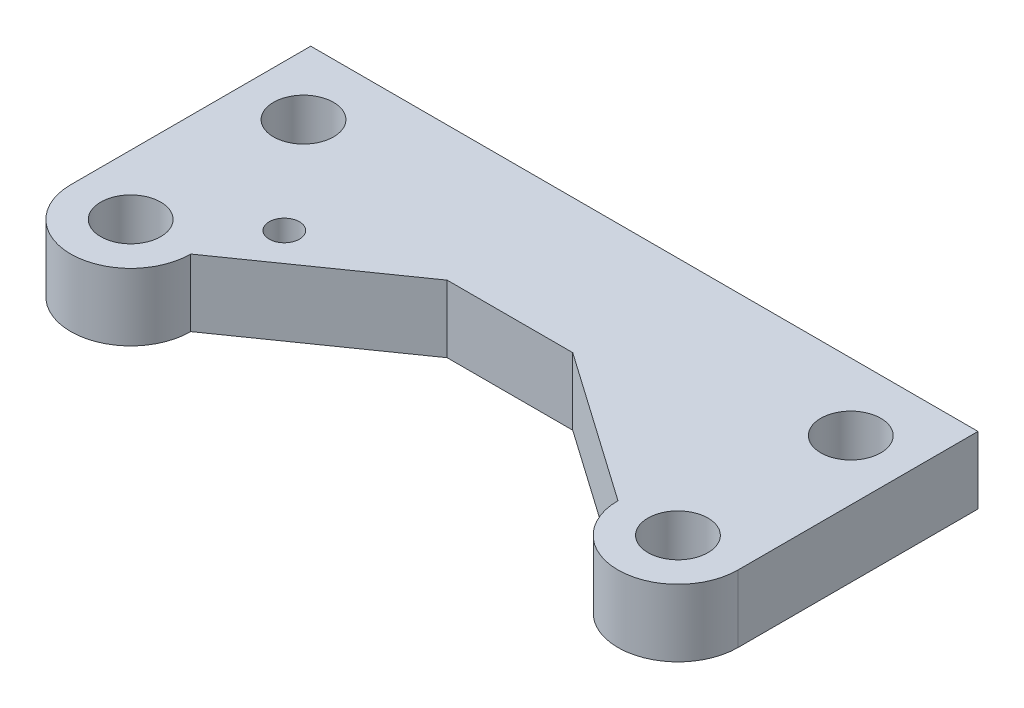
SolidWorks part; units mm, degrees
material "Custom Plastic"
ref_plane "X-Y Datum" through (0, 0, 0) normal (0, 0, 1) x (1, 0, 0)
ref_plane "X-Z Datum" through (0, 0, 0) normal (0, 1, 0) x (1, 0, 0)
ref_plane "Y-Z Datum" through (0, 0, 0) normal (1, 0, 0) x (0, 0, -1)
sketch "Sketch1" plane through (0, 0, 0) normal (0, 1, 0) x (1, 0, 0)
  line L0 (72.39, 0) -> (0, 0) construction
  line L1 (80.3275, 13.97) -> (-7.9375, 13.97) construction
  line L4 (80.3275, 31.75) -> (-7.9375, 31.75)
  line L6 (72.39, 22.86) -> (0, 22.86) construction
  line L7 (80.3275, 31.75) -> (80.3275, 13.97)
  line L8 (-7.9375, 31.75) -> (-7.9375, 13.97)
  line L10 (80.3275, 13.97) -> (80.3275, 0)
  line L12 (44.5013, 13.97) -> (27.8887, 13.97)
  line L14 (-7.9375, 0) -> (-7.9375, 13.97)
  line L16 (64.4525, 0) -> (44.5013, 13.97)
  line L17 (7.9375, 0) -> (27.8887, 13.97)
  circle A0 centre (0, 0) radius 3.9688
  circle A1 centre (72.39, 0) radius 3.9688
  circle A2 centre (72.39, 22.86) radius 3.9688
  circle A3 centre (0, 22.86) radius 3.9688
  arc A4 (80.3275, 0) -> (64.4525, 0) centre (72.39, 0) cw
  arc A5 (7.9375, 0) -> (-7.9375, 0) centre (0, 0) cw
  circle A6 centre (11.43, 8.89) radius 2
  dimension "D1" = 7.9375
  dimension "D2" = 7.9375
  dimension "D7" = 7.9375
  dimension "D8" = 7.9375
  dimension "D12" = 4
  dimension "D3" = 72.39
  dimension "D4" = 17.78
  dimension "D5" = 8.89
  dimension "D6" = 31.75
  dimension "D9" = 72.39
  dimension "D10" = 145
  dimension "D11" = 145
  dimension "D13" = 8.89
  dimension "D14" = 11.43
extrude "Boss-Extrude1" add sketch "Sketch1" against normal blind 8.89
